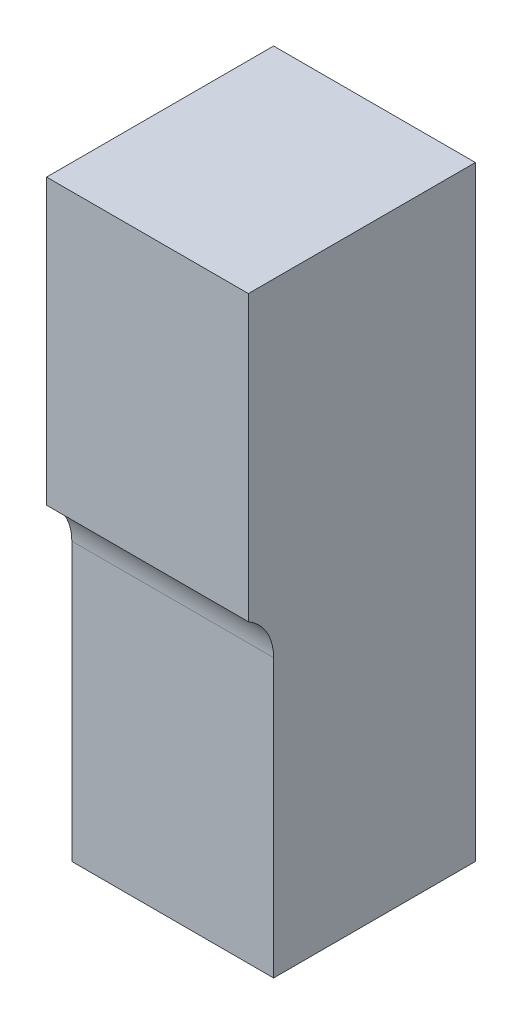
SolidWorks part; units mm, degrees
material "PE High Density"
ref_plane "Front Plane" through (0, 0, 0) normal (1, 0, 0) x (0, 1, 0)
ref_plane "Top Plane" through (0, 0, 0) normal (0, 0, 1) x (0, 1, 0)
ref_plane "Right Plane" through (0, 0, 0) normal (0, 1, 0) x (-1, 0, 0)
sketch "Sketch1" plane through (0, 0, 0) normal (1, 0, 0) x (0, 1, 0)
  line L0 (0, 0) -> (76.2, 0)
  line L1 (76.2, 0) -> (76.2, 28.575)
  line L2 (76.2, 28.575) -> (40.4243, 28.575)
  line L4 (34.925, 25.4) -> (0, 25.4)
  line L5 (0, 25.4) -> (0, 0)
  arc A0 (34.925, 25.4) -> (40.4243, 28.575) centre (34.925, 31.75) ccw
  point P5 (40.1711, 28.575)
  dimension "D5" = 6.35
  dimension "D1" = 76.2
  dimension "D2" = 3.175
  dimension "D3" = 25.4
  dimension "D4" = 34.925
extrude "Boss-Extrude1" add sketch "Sketch1" along normal blind 25.4 contours L0 L1 L2 A0 L4 L5
